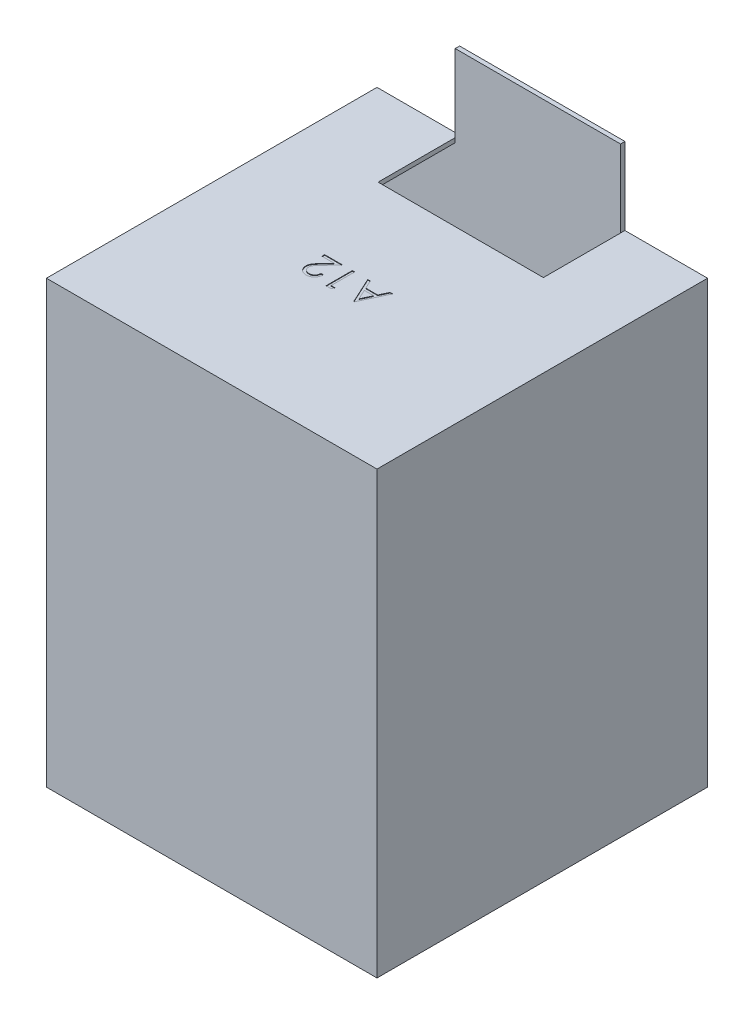
SolidWorks part; units mm, degrees
ref_plane "Plan de face" through (0, 0, 0) normal (0, 0, 1) x (1, 0, 0)
ref_plane "Plan de dessus" through (0, 0, 0) normal (0, 1, 0) x (1, 0, 0)
ref_plane "Plan de droite" through (0, 0, 0) normal (1, 0, 0) x (0, 0, -1)
sketch "Esquisse1" plane through (0, 0, 0) normal (0, 0, 1) x (1, 0, 0)
  line L1 (0, 0) -> (300, 0)
  line L2 (0, 0) -> (0, -400)
  line L3 (0, -400) -> (300, -400)
  line L4 (300, 0) -> (300, -400)
  dimension "D1" = 400
  dimension "D2" = 300
extrude "Boss.-Extru.1" add sketch "Esquisse1" along normal blind 300
sketch "Esquisse2" plane through (0, 0, 300) normal (0, 0, 1) x (1, 0, 0)
  line L8 (296, -4) -> (4, -4)
  line L9 (4, -4) -> (4, -396)
  line L10 (4, -396) -> (296, -396)
  line L11 (296, -396) -> (296, -4)
extrude "Enlèv. mat.-Extru.1" cut sketch "Esquisse2" against normal blind 296
sketch "Esquisse3" plane through (0, 0, 300) normal (0, 0, 1) x (1, 0, 0)
  line L1 (300, 0) -> (0, 0)
  line L2 (300, 0) -> (300, -400)
  line L3 (300, -400) -> (0, -400)
  line L4 (0, 0) -> (0, -400)
extrude "Boss.-Extru.2" add sketch "Esquisse3" against normal blind 4
sketch "Esquisse4" plane through (0, -400, 0) normal (0, -1, 0) x (-1, 0, 0)
  line L1 (-75, -74) -> (-225, -74)
  line L2 (-75, -74) -> (-75, -4)
  line L3 (-75, -4) -> (-225, -4)
  line L4 (-225, -74) -> (-225, -4)
  line L5 (0, 0) -> (-300, 0) construction
  line L6 (0, -300) -> (0, 0) construction
  line L7 (-300, -300) -> (-300, 0) construction
  dimension "D1" = 4
  dimension "D2" = 150
  dimension "D3" = 70
  dimension "D4" = 75
  dimension "D5" = 75
extrude "Enlèv. mat.-Extru.2" cut sketch "Esquisse4" against normal blind 4
sketch "Esquisse5" plane through (0, -4, 0) normal (0, -1, 0) x (1, 0, 0)
  line L1 (75, 74) -> (225, 74)
  line L2 (75, 74) -> (75, 4)
  line L3 (75, 4) -> (225, 4)
  line L4 (225, 74) -> (225, 4)
extrude "Enlèv. mat.-Extru.3" cut sketch "Esquisse5" against normal blind 4
sketch "Esquisse6" plane through (0, -400, 0) normal (0, -1, 0) x (-1, 0, 0)
  line L0 (0, 0) -> (-300, 0) construction
  line L1 (-75, -4) -> (-225, -4)
  line L2 (-75, -4) -> (-75, 0)
  line L3 (-75, 0) -> (-225, 0)
  line L4 (-225, -4) -> (-225, 0)
extrude "Boss.-Extru.3" add sketch "Esquisse6" along normal blind 70
sketch "Esquisse7" plane through (0, 0, 0) normal (0, 1, 0) x (1, 0, 0)
  line L1 (75, -4) -> (225, -4)
  line L2 (75, -4) -> (75, 0)
  line L3 (75, 0) -> (225, 0)
  line L4 (225, -4) -> (225, 0)
extrude "Boss.-Extru.4" add sketch "Esquisse7" along normal blind 70
sketch "Esquisse9" plane through (0, 0, 0) normal (0, 1, 0) x (1, 0, 0)
  text T0 "<r180>21 A" font "Century Gothic" height in points 90
extrude "Enlèv. mat.-Extru.4" cut sketch "Esquisse9" against normal blind 0.5
sketch "Esquisse10" plane through (0, -400, 0) normal (0, -1, 0) x (-1, 0, 0)
  text T0 "<r180>21 A</r>" font "Century Gothic" height in points 90
extrude "Enlèv. mat.-Extru.5" cut sketch "Esquisse10" against normal blind 0.5
